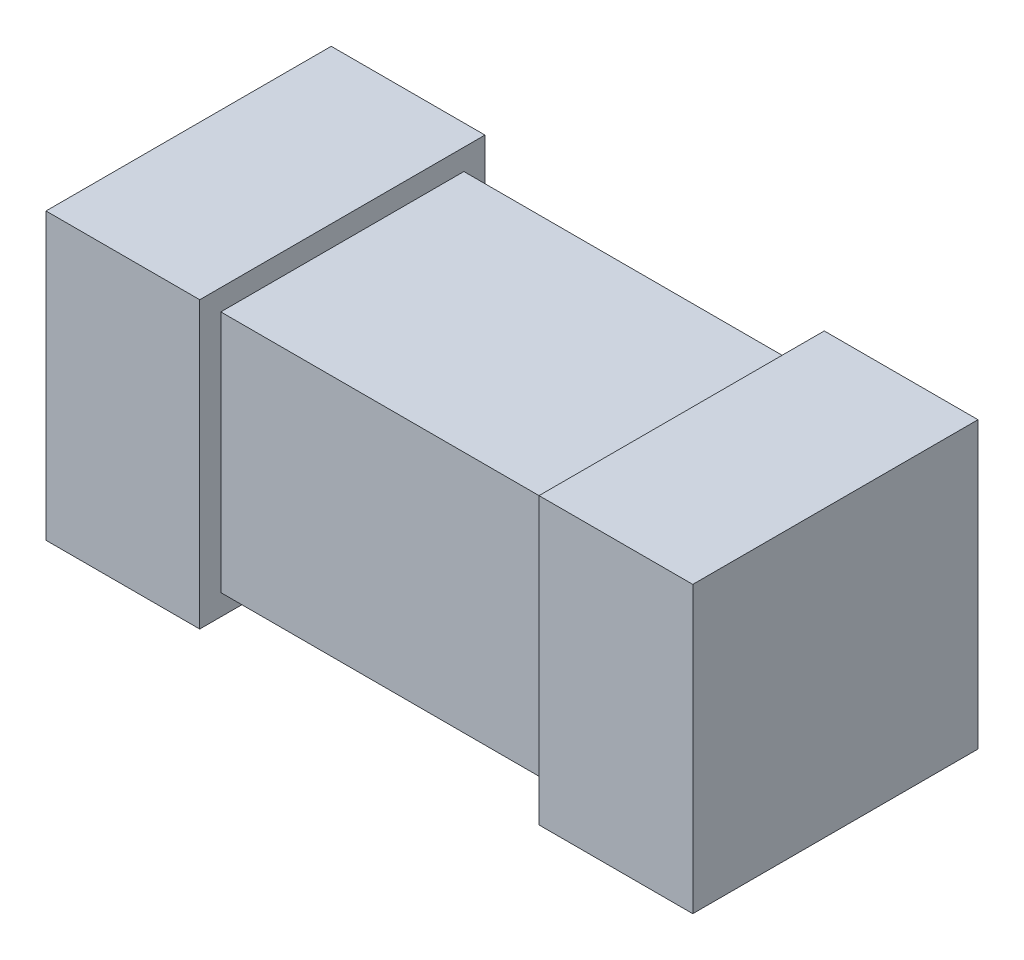
SolidWorks part; units mm, degrees
other "Детальный элемент1"
ref_plane "Спереди" through (0, 0, 0) normal (0, 0, 1) x (1, 0, 0)
ref_plane "Сверху" through (0, 0, 0) normal (0, 1, 0) x (1, 0, 0)
ref_plane "Справа" through (0, 0, 0) normal (1, 0, 0) x (0, 0, -1)
sketch "Эскиз1" plane through (0, 0, 0) normal (0, 0, 1) x (1, 0, 0)
  line L1 (1.6, -1.345) -> (3.05, -1.345)
  line L2 (1.6, -1.345) -> (1.6, 1.345)
  line L3 (1.6, 1.345) -> (3.05, 1.345)
  line L4 (3.05, -1.345) -> (3.05, 1.345)
  line L5 (1.6, -1.345) -> (3.05, 1.345) construction
  line L6 (1.6, 1.345) -> (3.05, -1.345) construction
  point P0 (2.325, 0)
  dimension "D1" = 2.69
  dimension "D2" = 1.45
  dimension "D3" = 2.325
extrude "Бобышка-Вытянуть1" add sketch "Эскиз1" along normal blind 2.69
sketch "Эскиз2" plane through (1.6, 0, 0) normal (-1, 0, 0) x (0, 0, 1)
  line L0 (0, 1.345) -> (2.69, -1.345) construction
  line L2 (0.1987, -1.1463) -> (2.4913, -1.1463)
  line L3 (0.1987, -1.1463) -> (0.1987, 1.1463)
  line L4 (0.1987, 1.1463) -> (2.4913, 1.1463)
  line L5 (2.4913, -1.1463) -> (2.4913, 1.1463)
  line L6 (0.1987, -1.1463) -> (2.4913, 1.1463) construction
  line L7 (0.1987, 1.1463) -> (2.4913, -1.1463) construction
  point P4 (1.345, 0)
  dimension "D1" = 2.2926
extrude "Бобышка-Вытянуть2" add sketch "Эскиз2" along normal up to surface (1.6 mm away) up to plane "Справа"
mirror "Зеркальное отражение1" about plane through (0, 0, 0) normal (1, 0, 0) of bodies 108
